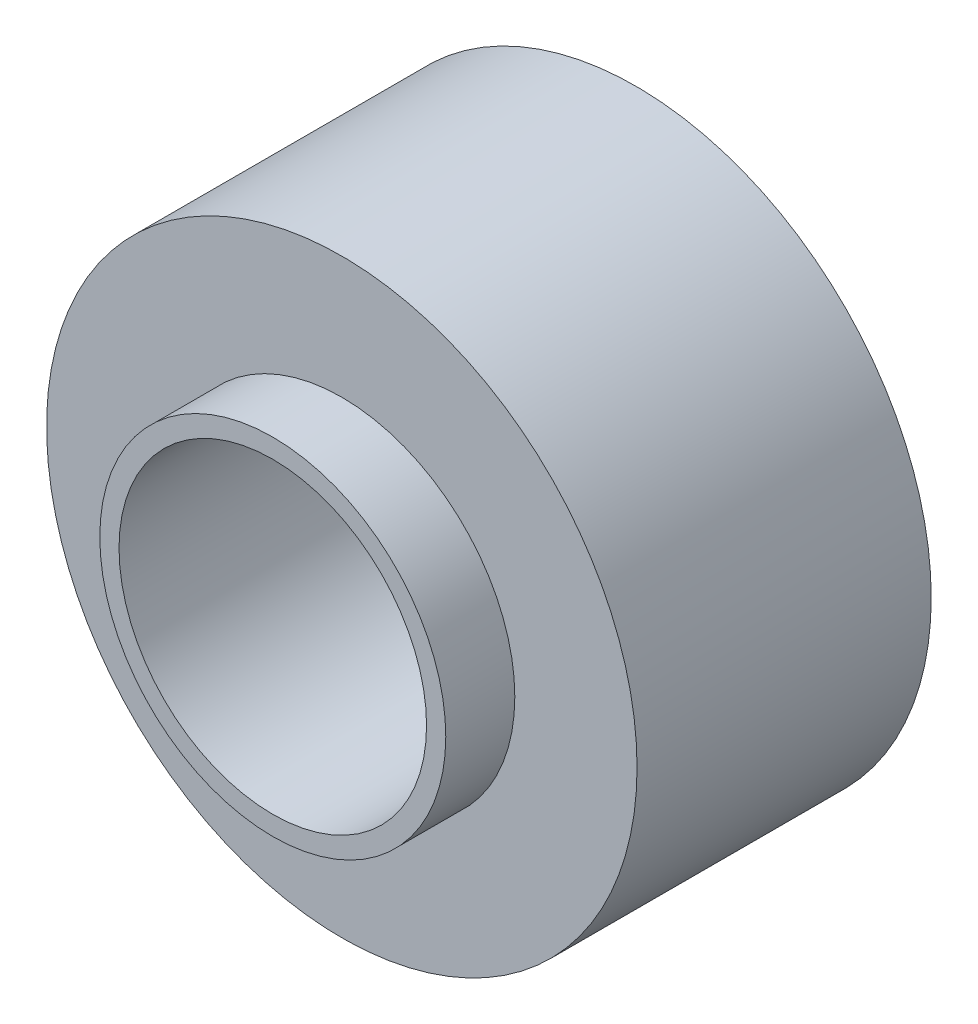
SolidWorks part; units mm, degrees
ref_plane "Front Plane" through (0, 0, 0) normal (0, 0, 1) x (1, 0, 0)
ref_plane "Top Plane" through (0, 0, 0) normal (0, 1, 0) x (1, 0, 0)
ref_plane "Right Plane" through (0, 0, 0) normal (1, 0, 0) x (0, 0, -1)
sketch "Sketch1" plane through (0, 0, 0) normal (0, 0, 1) x (1, 0, 0)
  line L0 (-107.3124, 0) -> (107.3124, 0) construction
  line L1 (0, -85.084) -> (0, 85.084) construction
  circle A0 centre (0, 0) radius 25.4
  circle A1 centre (0, 0) radius 28.575
  point P4 (0, 0)
  point P8 (0, 0)
  dimension "D1" = 50.8
  dimension "D2" = 3.175
extrude "Boss-Extrude1" add sketch "Sketch1" along normal mid plane 71.3994
sketch "Sketch2" plane through (0, 0, 0) normal (0, 0, 1) x (1, 0, 0)
  circle A0 centre (0, 0) radius 48.768
  circle A1 centre (0, 0) radius 28.575
  dimension "D1" = 97.536
extrude "Boss-Extrude2" add sketch "Sketch2" along normal mid plane 48.5902
